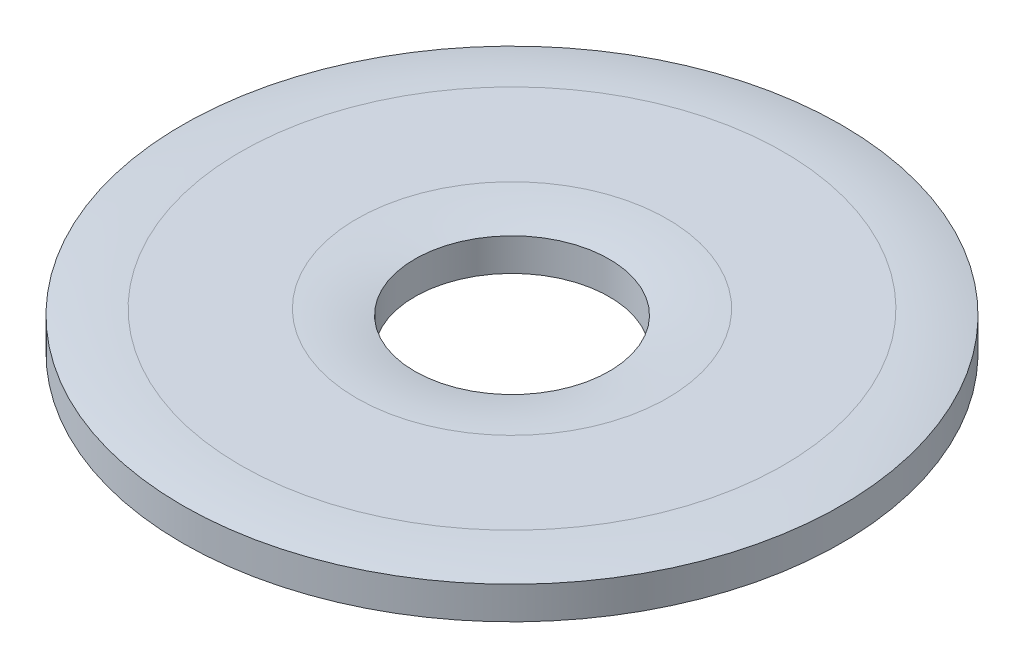
SolidWorks part; units mm, degrees
ref_plane "Front Plane" through (0, 0, 0) normal (0, 0, 1) x (1, 0, 0)
ref_plane "Top Plane" through (0, 0, 0) normal (0, 1, 0) x (1, 0, 0)
ref_plane "Right Plane" through (0, 0, 0) normal (1, 0, 0) x (0, 0, -1)
sketch "Sketch1" plane through (0, 0, 0) normal (0, 1, 0) x (1, 0, 0)
  circle A0 centre (0, 0) radius 8.7376
  circle A1 centre (0, 0) radius 2.5781
  dimension "OD" = 17.4752
  dimension "ID" = 5.1562
sketch "Sketch2" plane through (0, 0, 0) normal (1, 0, 0) x (0, 0, -1)
  line L0 (8.7376, 0.508) -> (8.7376, -0.508) construction
  line L1 (0, 0.508) -> (0, -0.508) construction
  point P2 (8.7376, 0)
  dimension "Thickness Range" = 1.016
sketch "Sketch3" plane through (0, 0, 0) normal (1, 0, 0) x (0, 0, -1)
  line L0 (8.7376, -0.508) -> (2.5781, -0.508)
  line L1 (2.5781, -0.508) -> (2.5781, 0.3556)
  line L2 (8.7376, -0.508) -> (8.7376, 0.3556)
  line L3 (8.7376, 0.508) -> (8.7376, -0.508) construction
  line L4 (8.7376, 0.508) -> (2.5781, 0.508) construction
  line L5 (2.5781, 0.508) -> (2.5781, -0.508) construction
  line L6 (4.118, 0.508) -> (7.1977, 0.508)
  line L7 (2.5781, -0.0762) -> (4.118, -0.0762) construction
  line L8 (4.118, -0.0762) -> (5.6578, -0.0762) construction
  line L9 (5.6578, -0.0762) -> (7.1977, -0.0762) construction
  line L10 (7.1977, -0.0762) -> (8.7376, -0.0762) construction
  arc A1 (4.118, 0.508) -> (2.5781, 0.3556) centre (4.118, -7.3478) ccw
  arc A2 (7.1977, 0.508) -> (8.7376, 0.3556) centre (7.1977, -7.3478) cw
  point P12 (2.5781, 0)
  point P14 (5.6578, 0.508)
  dimension "D1" = 0.8636
revolve "Revolve1" add sketch "Sketch3" angle 360 about L1
equation "\"D1@Sketch3\"=\"Thickness Range@Sketch2\"*.85"
